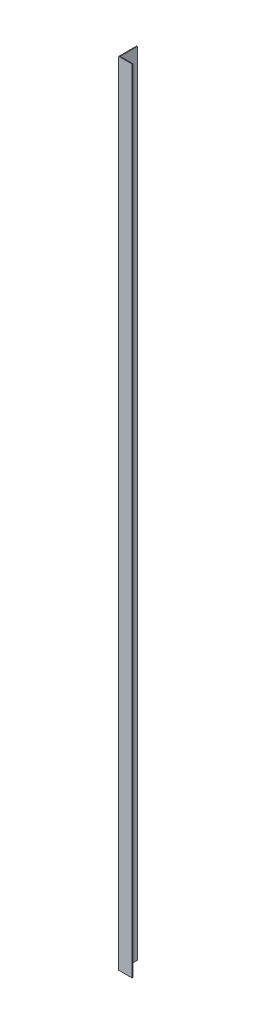
SolidWorks part; units mm, degrees
ref_plane "Front Plane" through (0, 0, 0) normal (0, 0, 1) x (1, 0, 0)
ref_plane "Top Plane" through (0, 0, 0) normal (0, 1, 0) x (1, 0, 0)
ref_plane "Right Plane" through (0, 0, 0) normal (1, 0, 0) x (0, 0, -1)
other "Configuration Table"
sketch "Sketch1" plane through (0, 0, 0) normal (0, 1, 0) x (1, 0, 0)
  line L0 (700, -40) -> (700, -38.5)
  line L1 (700, -38.5) -> (671.5, -38.5)
  line L2 (671.5, -38.5) -> (671.5, 0)
  line L3 (671.5, 0) -> (670, 0)
  line L4 (670, 0) -> (670, -40)
  line L5 (670, -40) -> (700, -40)
extrude "TOPPING_sove_sag_1" add sketch "Sketch1" along normal blind 1770 from offset 200 separate body
